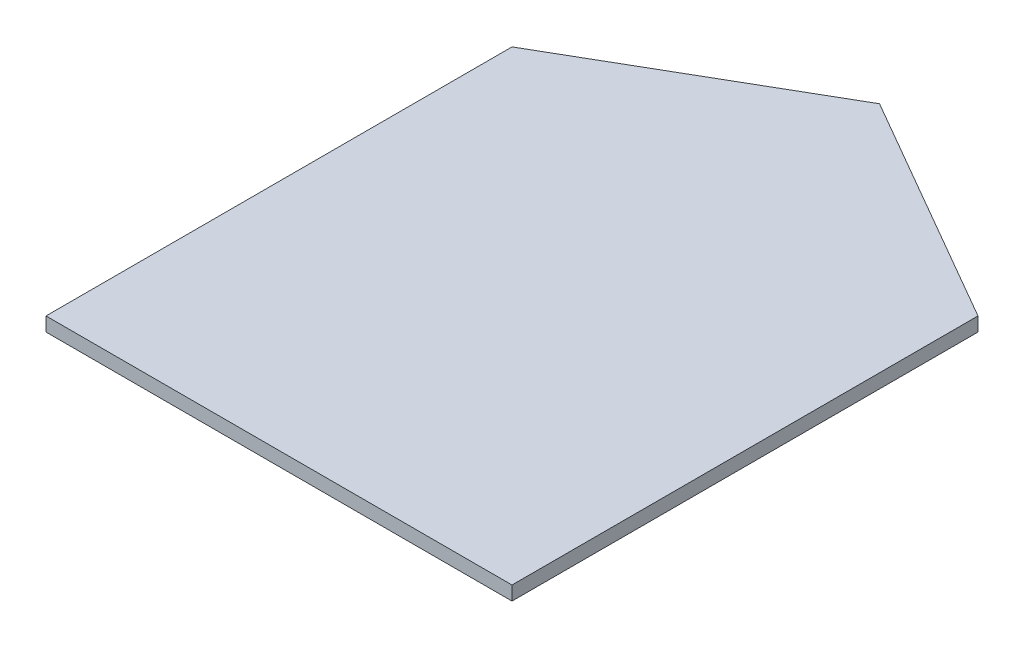
SolidWorks part; units mm, degrees
material "Ti-6Al-4VSolution treated and aged (SS)"
ref_plane "Front Plane" through (0, 0, 0) normal (0, 0, 1) x (1, 0, 0)
ref_plane "Top Plane" through (0, 0, 0) normal (0, 1, 0) x (1, 0, 0)
ref_plane "Right Plane" through (0, 0, 0) normal (1, 0, 0) x (0, 0, -1)
sketch "Sketch2" plane through (0, 0, 0) normal (0, 1, 0) x (1, 0, 0)
  line L0 (0, 0) -> (100, 0)
  line L1 (100, 0) -> (100, 100)
  line L2 (100, 100) -> (50, 128.8675)
  line L3 (50, 128.8675) -> (0, 100)
  line L4 (0, 100) -> (0, 0)
  point P3 (50, 0)
  dimension "D1" = 100
  dimension "D2" = 128.8675
  dimension "D3" = 120
extrude "Boss-Extrude1" add sketch "Sketch2" along normal blind 3
